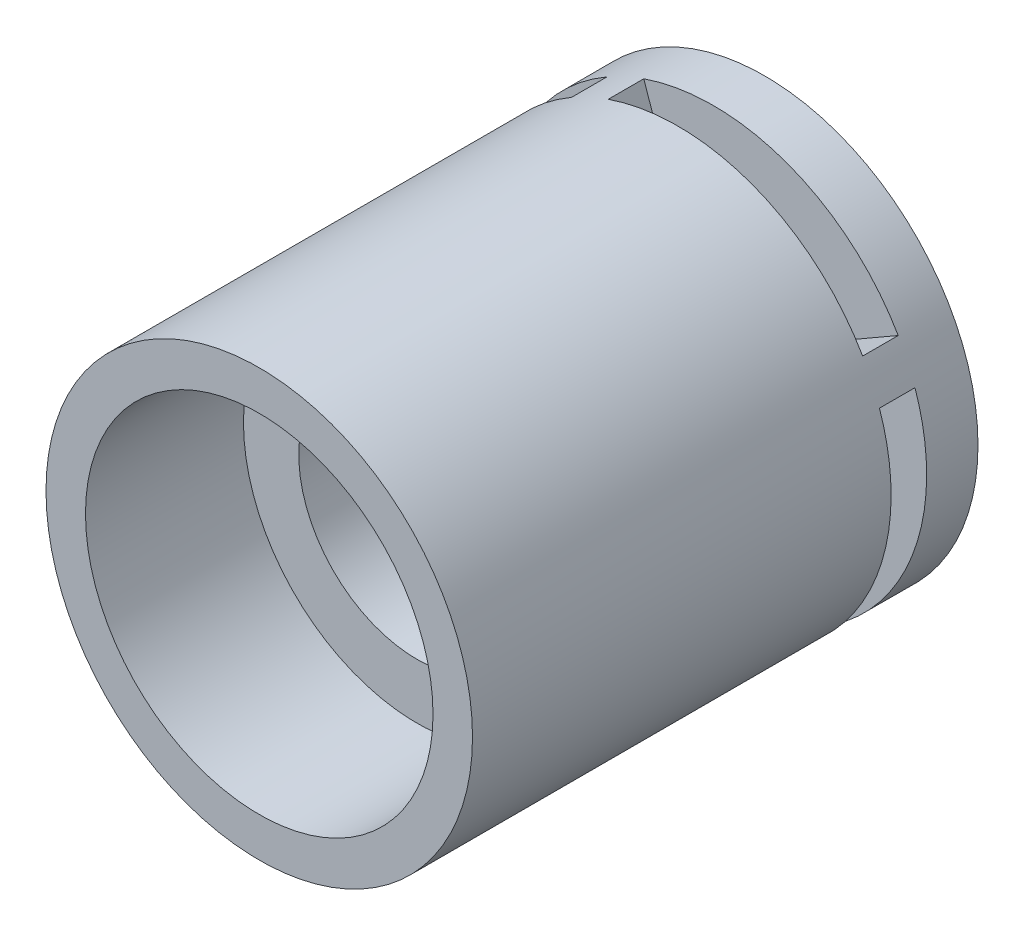
SolidWorks part; units mm, degrees
ref_plane "Front Plane" through (0, 0, 0) normal (0, 0, 1) x (1, 0, 0)
ref_plane "Top Plane" through (0, 0, 0) normal (0, 1, 0) x (1, 0, 0)
ref_plane "Right Plane" through (0, 0, 0) normal (1, 0, 0) x (0, 0, -1)
sketch "Sketch2" plane through (0, 0, 0) normal (0, 0, 1) x (1, 0, 0)
  circle A0 centre (0, 0) radius 13.5
  dimension "D1" = 27
extrude "Boss-Extrude1" add sketch "Sketch2" against normal blind 32
ref_plane "Plane1" through (0, 0, 0) normal (0, 0, 1) x (1, 0, 0)
sketch "Sketch4" plane through (0, 0, 0) normal (0, 0, 1) x (1, 0, 0)
  circle A0 centre (0, 0) radius 11
  dimension "D1" = 22
extrude "Cut-Extrude1" cut sketch "Sketch4" against normal blind 10
sketch "Sketch5" plane through (0, 0, 0) normal (0, 0, 1) x (1, 0, 0)
  circle A0 centre (0, 0) radius 7.5
  dimension "D1" = 15
extrude "Cut-Extrude2" cut sketch "Sketch5" against normal blind 30
sketch "Sketch9" plane through (0, 0, -32) normal (0, 0, -1) x (-1, 0, 0)
  line L0 (0, -18.8285) -> (0, 25.3406) construction
sketch3d "3DSketch4"
  point P0 (4.7437, 12.6391, -18.7172)
ref_plane "Plane5" through (0, 13.5, 0) normal (0, 1, 0) x (1, 0, 0)
sketch "Sketch10" plane through (0, 13.5, 0) normal (0, 1, 0) x (1, 0, 0)
  line L0 (13.5, 32) -> (-13.5, 32) construction
  line L1 (-4.4913, 28.75) -> (14.1517, 28.75)
  line L2 (-4.4913, 28.75) -> (-4.4913, 26.5)
  line L3 (-4.4913, 26.5) -> (14.1517, 26.5)
  line L4 (14.1517, 28.75) -> (14.1517, 26.5)
  dimension "D1" = 18.643
  dimension "D2" = 2.25
  dimension "D3" = 3.25
wrap "Wrap1" sketch "Sketch10" wrap type deboss source sketch "Sketch10" thickness 12 face at (13.5, 0, -32) parameters "D1"=12
pattern_circular "CirPattern1" count 4 over 360 about axis through (0, 0, -32) along (0, 0, 1) of "Wrap1"
